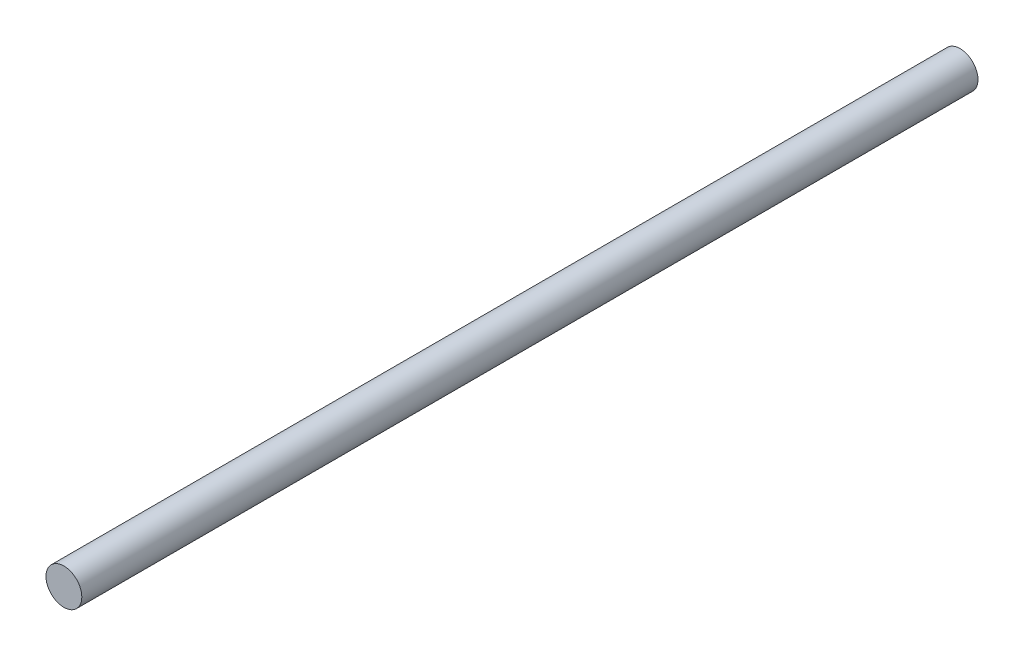
SolidWorks part; units mm, degrees
ref_plane "前视基准面" through (0, 0, 0) normal (0, 0, 1) x (1, 0, 0)
ref_plane "上视基准面" through (0, 0, 0) normal (0, 1, 0) x (1, 0, 0)
ref_plane "右视基准面" through (0, 0, 0) normal (1, 0, 0) x (0, 0, -1)
sketch "草图1" plane through (0, 0, 0) normal (0, 0, 1) x (1, 0, 0)
  circle A0 centre (0, 0) radius 6
  dimension "D1" = 12
extrude "凸台-拉伸1" add sketch "草图1" along normal blind 300
